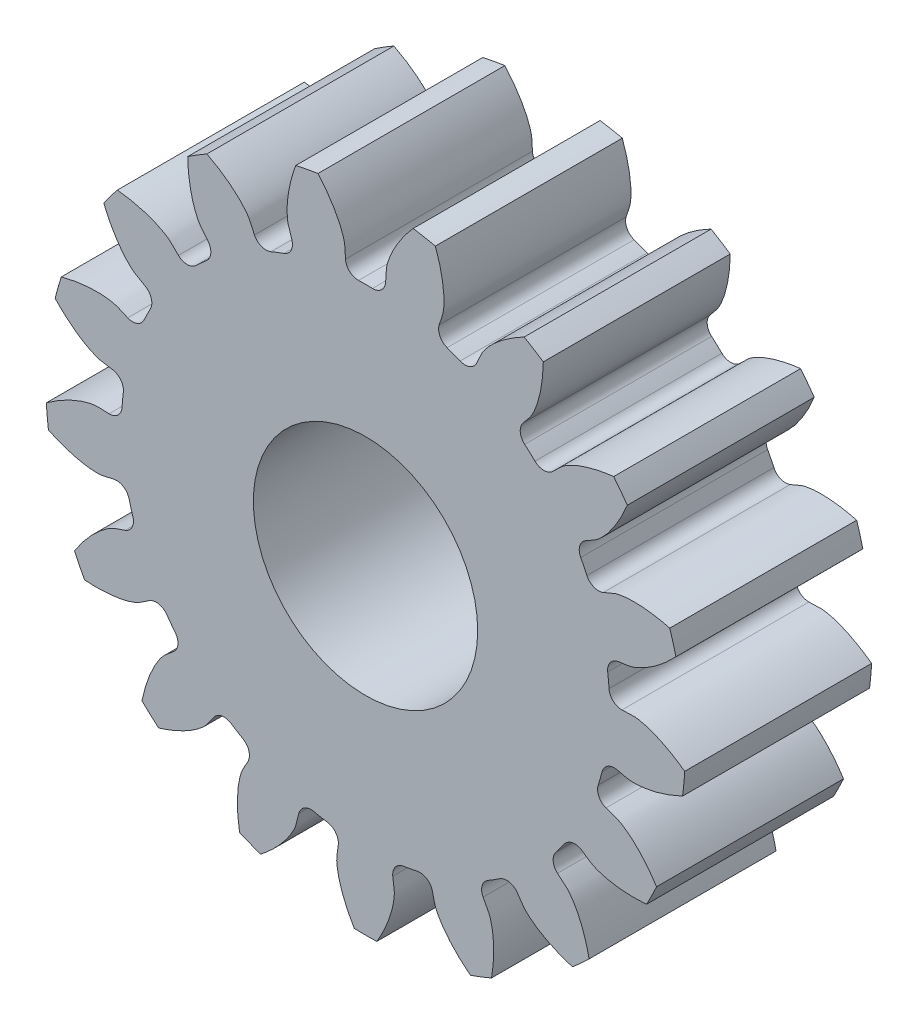
SolidWorks part; units mm, degrees
ref_plane "前视基准面" through (0, 0, 0) normal (0, 0, 1) x (1, 0, 0)
ref_plane "上视基准面" through (0, 0, 0) normal (0, 1, 0) x (1, 0, 0)
ref_plane "右视基准面" through (0, 0, 0) normal (1, 0, 0) x (0, 0, -1)
other "Configuration Table"
ref_axis "Axis1" through (0, 0, -88.99) along (0, 0, 1)
sketch "草图1" plane through (0, 0, 0) normal (0, 0, 1) x (1, 0, 0)
  circle A0 centre (0, 0) radius 8.55
extrude "LaShenA" add sketch "草图1" along normal blind 5
sketch "SketchA" plane through (0, 0, 5) normal (0, 0, 1) x (1, 0, 0)
  line L0 (0, 0) -> (0, 8.55) construction
  arc A0 (0.1863, 6.5223) -> (-0.1863, 6.5223) centre (0, 0) ccw
  arc A1 (1.7355, 8.9151) -> (-1.7355, 8.9151) centre (0, 0) ccw
  arc A2 (-0.1863, 6.5223) -> (-0.5371, 6.8384) centre (-0.1961, 6.8642) cw
  arc A3 (0.5371, 6.8384) -> (0.1863, 6.5223) centre (0.1961, 6.8642) cw
  circle A4 centre (0, 0) radius 7.1886 construction
  circle A5 centre (0, 0) radius 8.55 construction
  circle A6 centre (0, 0) radius 6.525 construction
  circle A7 centre (0, 0) radius 7.65 construction
  spline S0 degree 3 poles (0.5371, 6.8384) (0.5454, 6.9485) (0.5423, 7.0828) (0.5666, 7.2261) (0.578, 7.2727) (0.588, 7.3096) (0.6007, 7.3519) (0.6165, 7.3993) (0.6357, 7.4518) (0.6585, 7.5091) (0.6853, 7.5712) (0.7163, 7.6379) (0.7518, 7.7089) (0.7922, 7.784) (0.8376, 7.863) (0.8883, 7.9458) (0.9446, 8.0319) (1.0066, 8.1213) (1.0747, 8.2135) (1.149, 8.3085) (1.2298, 8.4057) (1.3172, 8.5051) (1.4114, 8.6062) (1.5491, 8.7457) (1.659, 8.8478) (1.7355, 8.9151) knots 0.121184 0.121184 0.121184 0.121184 0.238206 0.264317 0.275812 0.289397 0.305072 0.322837 0.342692 0.364637 0.388672 0.414798 0.443013 0.473318 0.505713 0.540198 0.576773 0.615438 0.656194 0.699039 0.743974 0.790999 0.840114 0.89132 1 1 1 1
  spline S1 degree 3 poles (-0.5371, 6.8384) (-0.5454, 6.9485) (-0.5423, 7.0828) (-0.5666, 7.2261) (-0.578, 7.2727) (-0.588, 7.3096) (-0.6007, 7.3519) (-0.6165, 7.3993) (-0.6357, 7.4518) (-0.6585, 7.5091) (-0.6853, 7.5712) (-0.7163, 7.6379) (-0.7518, 7.7089) (-0.7922, 7.784) (-0.8376, 7.863) (-0.8883, 7.9458) (-0.9446, 8.0319) (-1.0066, 8.1213) (-1.0747, 8.2135) (-1.149, 8.3085) (-1.2298, 8.4057) (-1.3172, 8.5051) (-1.4114, 8.6062) (-1.5491, 8.7457) (-1.659, 8.8478) (-1.7355, 8.9151) knots 0.121184 0.121184 0.121184 0.121184 0.238206 0.264317 0.275812 0.289397 0.305072 0.322837 0.342692 0.364637 0.388672 0.414798 0.443013 0.473318 0.505713 0.540198 0.576773 0.615438 0.656194 0.699039 0.743974 0.790999 0.840114 0.89132 1 1 1 1
  dimension "D1" = 0.342
  dimension "Db" = 14.3773
  dimension "Da" = 17.1
  dimension "Df" = 13.05
  dimension "Dn" = 15.3
extrude "Cut-ExtrudeA" cut sketch "SketchA" against normal blind 5
pattern_circular "www.KYTool.cn" count 17 over 360 about axis through (0, 0, -88.99) along (0, 0, 1) of "Cut-ExtrudeA"
sketch "草图3" plane through (0, 0, 5) normal (0, 0, 1) x (1, 0, 0)
  circle A0 centre (0, 0) radius 3
  dimension "D1" = 6
extrude "切除-拉伸2" cut sketch "草图3" against normal through all
